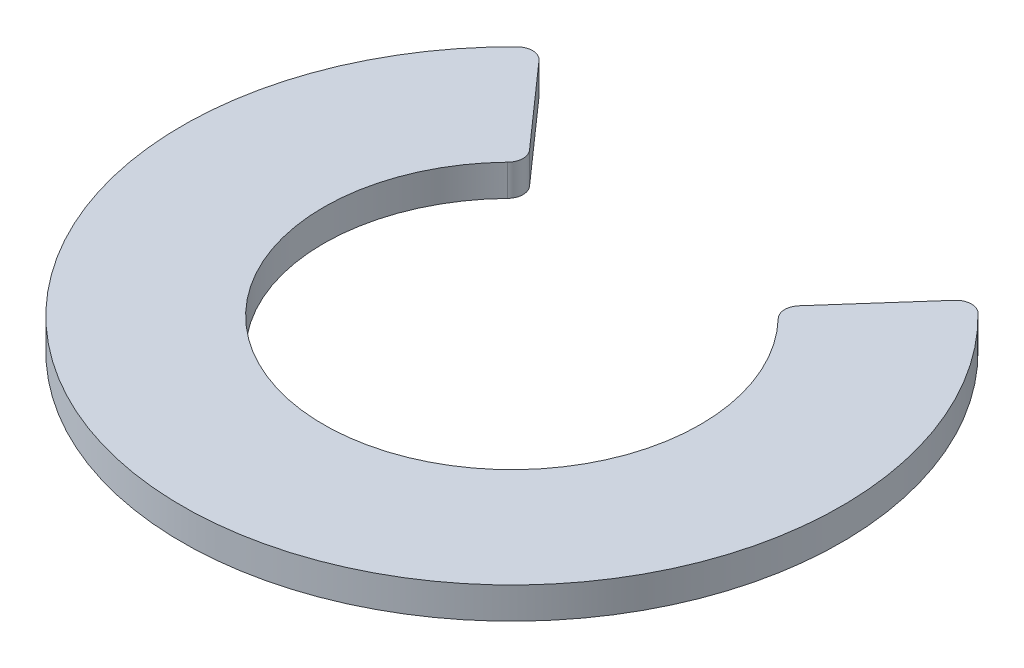
SolidWorks part; units mm, degrees
ref_plane "Front Plane" through (0, 0, 0) normal (0, 0, 1) x (1, 0, 0)
ref_plane "Top Plane" through (0, 0, 0) normal (0, 1, 0) x (1, 0, 0)
ref_plane "Right Plane" through (0, 0, 0) normal (1, 0, 0) x (0, 0, -1)
sketch "Sketch1" plane through (0, 0, 0) normal (0, 1, 0) x (1, 0, 0)
  line L0 (-1.3915, 1.5728) -> (-0.7951, 0.8988)
  line L1 (0.7951, 0.8988) -> (1.3915, 1.5728)
  line L2 (0, 0) -> (0, 0.8997) construction
  arc A0 (-0.7951, 0.8988) -> (0.7951, 0.8988) centre (0, 0) ccw
  arc A1 (-1.3915, 1.5728) -> (1.3915, 1.5728) centre (0, 0) ccw
  dimension "D1" = 2.4
  dimension "D2" = 4.2
extrude "Boss-Extrude1" add sketch "Sketch1" along normal blind 0.2
fillet "Fillet1" radius 0.1 4 edges at (0.7951, 0.1, -0.8988) (1.3915, 0.1, -1.5728) (-1.3915, 0.1, -1.5728) (-0.7951, 0.1, -0.8988)
